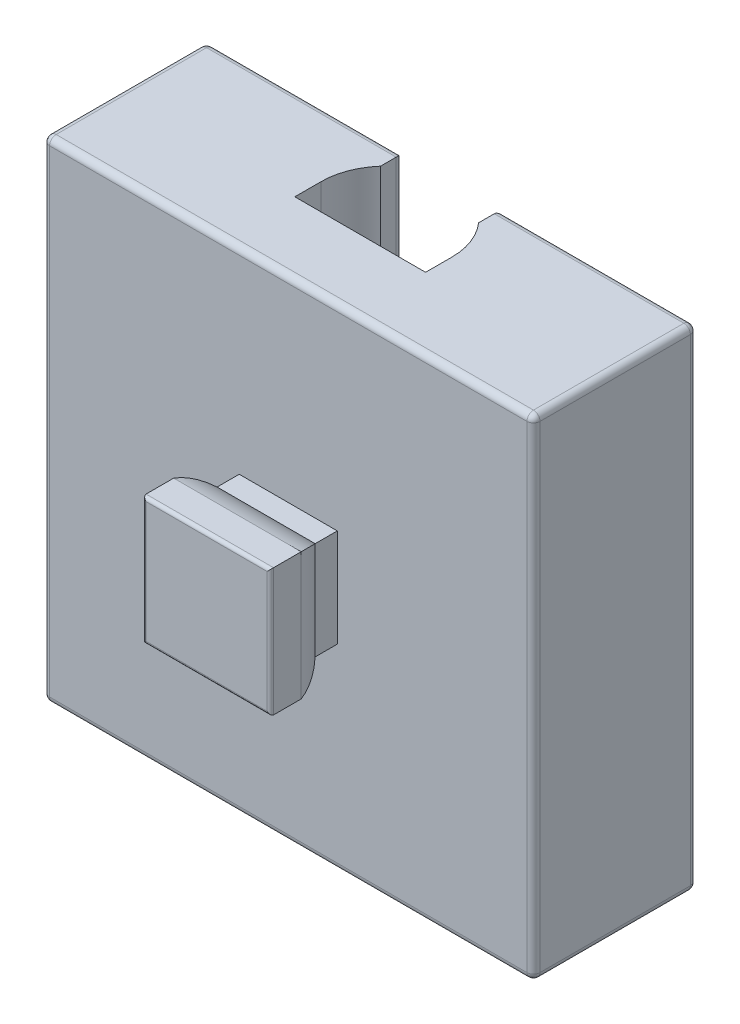
SolidWorks part; units mm, degrees
ref_plane "前视基准面" through (0, 0, 0) normal (0, 0, 1) x (1, 0, 0)
ref_plane "上视基准面" through (0, 0, 0) normal (0, 1, 0) x (1, 0, 0)
ref_plane "右视基准面" through (0, 0, 0) normal (1, 0, 0) x (0, 0, -1)
sketch "草图1" plane through (0, 0, 0) normal (0, 0, 1) x (1, 0, 0)
  line L1 (-7.5, -7.5) -> (7.5, -7.5)
  line L2 (-7.5, -7.5) -> (-7.5, 7.5)
  line L3 (-7.5, 7.5) -> (7.5, 7.5)
  line L4 (7.5, -7.5) -> (7.5, 7.5)
extrude "凸台-拉伸1" add sketch "草图1" against normal blind 5
sketch "草图2" plane through (0, 0, 0) normal (0, 0, 1) x (1, 0, 0)
  line L1 (-1.5, -1.5) -> (1.5, -1.5)
  line L2 (-1.5, -1.5) -> (-1.5, 1.5)
  line L3 (-1.5, 1.5) -> (1.5, 1.5)
  line L4 (1.5, -1.5) -> (1.5, 1.5)
extrude "凸台-拉伸2" add sketch "草图2" along normal blind 1
sketch "草图3" plane through (0, 0, 0) normal (0, 1, 0) x (1, 0, 0)
  line L0 (-1.95, -2.5) -> (1.95, -2.5)
  line L1 (-1.95, -2.5) -> (-1.95, -1.5556)
  line L2 (-1.5, -1) -> (-1.5, 0) construction
  line L3 (-1.5, -0.6771) -> (1.5, -0.6771)
  line L4 (1.95, -2.5) -> (1.95, -1.5556)
  arc A0 (1.95, -1.5556) -> (1.5, -0.6771) centre (0, -2) ccw
  arc A1 (-1.5, -0.6771) -> (-1.95, -1.5556) centre (0, -2) ccw
extrude "凸台-拉伸3" add sketch "草图3" along normal blind 2 and the other way blind 2
sketch "草图4" plane through (0, 0, 0) normal (1, 0, 0) x (0, 0, -1)
  line L0 (-2.5, 1.95) -> (-1.5556, 1.95)
  line L1 (-2.5, 1.95) -> (-2.5, 2)
  line L2 (-2.5, -2) -> (-2.5, 2) construction
  line L3 (-2.5, 2) -> (-0.6771, 2)
  line L4 (-0.6771, 2) -> (-0.6771, 1.5)
  line L5 (-2.5, -2) -> (-0.6771, -2)
  line L6 (-0.6771, -2) -> (-0.6771, -1.5)
  line L7 (-2.5, -1.95) -> (-1.5556, -1.95)
  line L8 (-2.5, -1.95) -> (-2.5, -2)
  arc A0 (-0.6771, 1.5) -> (-1.5556, 1.95) centre (-2, 0) ccw
  arc A2 (-1.5556, -1.95) -> (-0.6771, -1.5) centre (-2, 0) ccw
extrude "切除-拉伸1" cut sketch "草图4" against normal up to next and the other way up to next
sketch "草图5" plane through (0, -7.5, 0) normal (0, -1, 0) x (1, 0, 0)
  line L0 (-1.5, -5) -> (-1.5, -4.3229)
  line L1 (-7.5, -5) -> (7.5, -5) construction
  line L2 (1.5, -5) -> (1.5, -4.3229)
  line L3 (-2, -3) -> (-2, -2.2)
  line L4 (2, -3) -> (2, -2.2)
  line L5 (2, -2.2) -> (-2, -2.2)
  line L6 (-1.5, -5) -> (1.5, -5)
  arc A0 (-2, -3) -> (-1.5, -4.3229) centre (0, -3) ccw
  arc A1 (1.5, -4.3229) -> (2, -3) centre (0, -3) ccw
extrude "切除-拉伸2" cut sketch "草图5" against normal up to next
fillet "圆角1" radius 0.1 4 edges at (0, -1.95, 2.5) (-1.95, 0, 2.5) (0, 1.95, 2.5) (1.95, 0, 2.5)
fillet "圆角2" radius 0.2 16 edges at (7.5, 0, 0) (0, -7.5, 0) (-7.5, 0, 0) (0, 7.5, 0) (-7.5, 7.5, -2.5) (7.5, 7.5, -2.5) (-7.5, -7.5, -2.5) (7.5, -7.5, -2.5) (-4.5, 7.5, -5) (-7.5, 0, -5) (-4.5, -7.5, -5) (4.5, -7.5, -5) (7.5, 0, -5) (4.5, 7.5, -5) (1.5, 0, -5) (-1.5, 0, -5)
